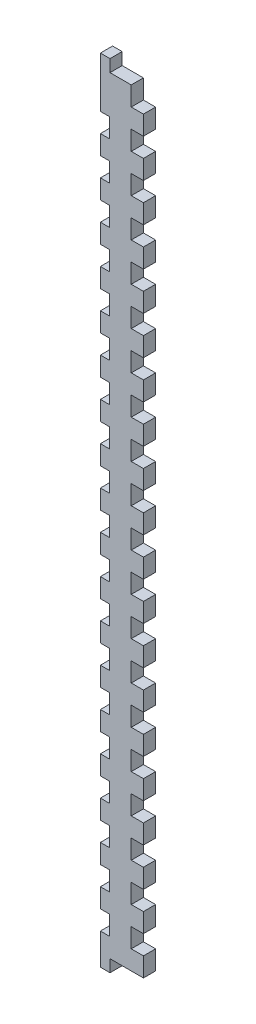
SolidWorks part; units mm, degrees
ref_plane "Front Plane" through (0, 0, 0) normal (0, 0, 1) x (1, 0, 0)
ref_plane "Top Plane" through (0, 0, 0) normal (0, 1, 0) x (1, 0, 0)
ref_plane "Right Plane" through (0, 0, 0) normal (1, 0, 0) x (0, 0, -1)
sketch "Sketch1" plane through (0, 0, 0) normal (0, 0, 1) x (1, 0, 0)
  line L1 (-11.2141, -200) -> (11.2141, -200)
  line L2 (-11.2141, -200) -> (-11.2141, 200)
  line L3 (-11.2141, 200) -> (11.2141, 200)
  line L4 (11.2141, -200) -> (11.2141, 200)
  line L5 (-11.2141, -200) -> (11.2141, 200) construction
  line L6 (-11.2141, 200) -> (11.2141, -200) construction
  point P0 (0, 0)
  dimension "D1" = 22.4282
  dimension "D2" = 400
extrude "Boss-Extrude1" add sketch "Sketch1" along normal blind 6.35
sketch "Sketch2" plane through (0, 0, 6.35) normal (0, 0, 1) x (1, 0, 0)
  line L1 (-6.5913, -180) -> (-11.2141, -180)
  line L2 (-6.5913, -180) -> (-6.5913, -190)
  line L3 (-6.5913, -190) -> (-11.2141, -190)
  line L4 (-11.2141, -180) -> (-11.2141, -190)
  line L6 (-11.2141, 200) -> (-11.2141, -200) construction
  line L13 (-11.2141, -200) -> (11.2141, -200) construction
  point P8 (-6.5913, -185)
  dimension "D2" = 4.6228
  dimension "D3" = 10
  dimension "D1" = 10
extrude "Cut-Extrude2" cut sketch "Sketch2" against normal blind 6.35
sketch "Sketch13" plane through (0, 0, 6.35) normal (0, 0, 1) x (1, 0, 0)
  line L0 (11.2141, -200) -> (11.2141, 200) construction
  line L1 (4.8641, -190) -> (11.2141, -190)
  line L2 (4.8641, -190) -> (4.8641, -180)
  line L3 (4.8641, -180) -> (11.2141, -180)
  line L4 (11.2141, -190) -> (11.2141, -180)
  line L5 (-6.5913, -180) -> (-11.2141, -180) construction
  line L7 (-11.2141, -190) -> (-6.5913, -190) construction
  dimension "D1" = 6.35
extrude "Cut-Extrude4" cut sketch "Sketch13" against normal blind 6.35
pattern_linear "LPattern1" count 19 spacing 20 along (0, 1, 0) of "Cut-Extrude2"
pattern_linear "LPattern2" count 20 spacing 20 along (0, 1, 0) of "Cut-Extrude4"
sketch "Sketch14" plane through (0, 0, 0) normal (0, 0, 1) x (1, 0, 0)
  line L0 (-11.2141, -200) -> (11.2141, -200) construction
  line L1 (-11.2141, 200) -> (-6.2103, 200)
  line L2 (-11.2141, 200) -> (-11.2141, 206.35)
  line L3 (-11.2141, 206.35) -> (-6.2103, 206.35)
  line L4 (-6.2103, 200) -> (-6.2103, 206.35)
  line L5 (-11.2141, -200) -> (-6.2103, -200)
  line L6 (-11.2141, -200) -> (-11.2141, -206.35)
  line L7 (-11.2141, -206.35) -> (-6.2103, -206.35)
  line L8 (-6.2103, -200) -> (-6.2103, -206.35)
  line L9 (4.8641, 200) -> (-11.2141, 200) construction
  dimension "D1" = 6.35
  dimension "D2" = 6.35
  dimension "D3" = 5.0038
  dimension "D4" = 5.0038
extrude "Boss-Extrude4" add sketch "Sketch14" along normal blind 6.35
equation "\"z\"= 40cm"
equation "\"D2@Sketch1\"=\"z\""
equation "\"tWidth\"= 1cm"
equation "\"tHeight02\"= 0.182in"
equation "\"D3@Sketch2\"=\"tWidth\""
equation "\"tHeight01\"= .25in"
equation "\"D2@Sketch2\"=\"tHeight02\""
equation "\"D1@Cut-Extrude2\"=\"tHeight01\""
equation "\"D1@Sketch13\"=\"tHeight01\""
equation "\"D1@Cut-Extrude4\"=\"tHeight01\""
equation "\"D1@Sketch2\"=\"tWidth\""
equation "\"D1@Boss-Extrude4\"=\"tHeight01\""
equation "\"D2@Sketch14\"=\"tHeight01\""
equation "\"D1@Sketch14\"=\"tHeight01\""
